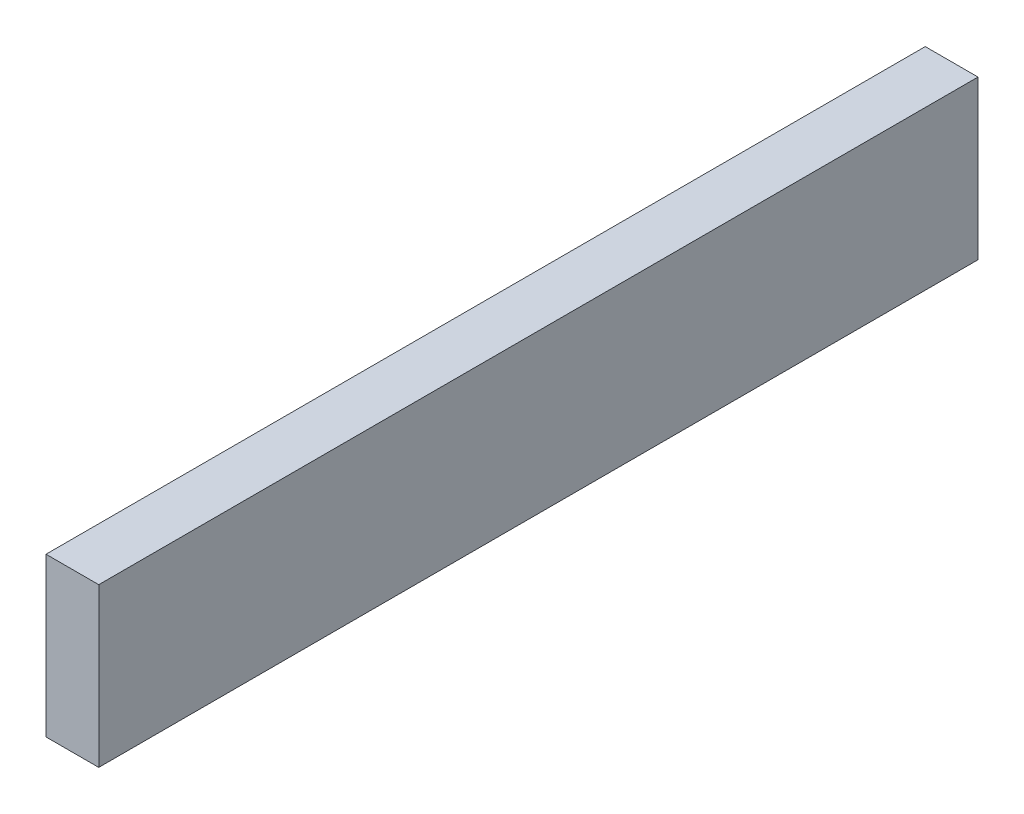
SolidWorks part; units mm, degrees
ref_plane "Front Plane" through (0, 0, 0) normal (0, 0, 1) x (1, 0, 0)
ref_plane "Top Plane" through (0, 0, 0) normal (0, 1, 0) x (1, 0, 0)
ref_plane "Right Plane" through (0, 0, 0) normal (1, 0, 0) x (0, 0, -1)
sketch "Sketch1" plane through (0, 0, 0) normal (0, 0, 1) x (1, 0, 0)
  line L1 (-15, -45) -> (15, -45)
  line L2 (-15, -45) -> (-15, 45)
  line L3 (-15, 45) -> (15, 45)
  line L4 (15, -45) -> (15, 45)
  line L5 (-15, -45) -> (15, 45) construction
  line L6 (-15, 45) -> (15, -45) construction
  point P0 (0, 0)
  dimension "D1" = 30
  dimension "D2" = 90
extrude "Boss-Extrude1" add sketch "Sketch1" along normal mid plane 500
